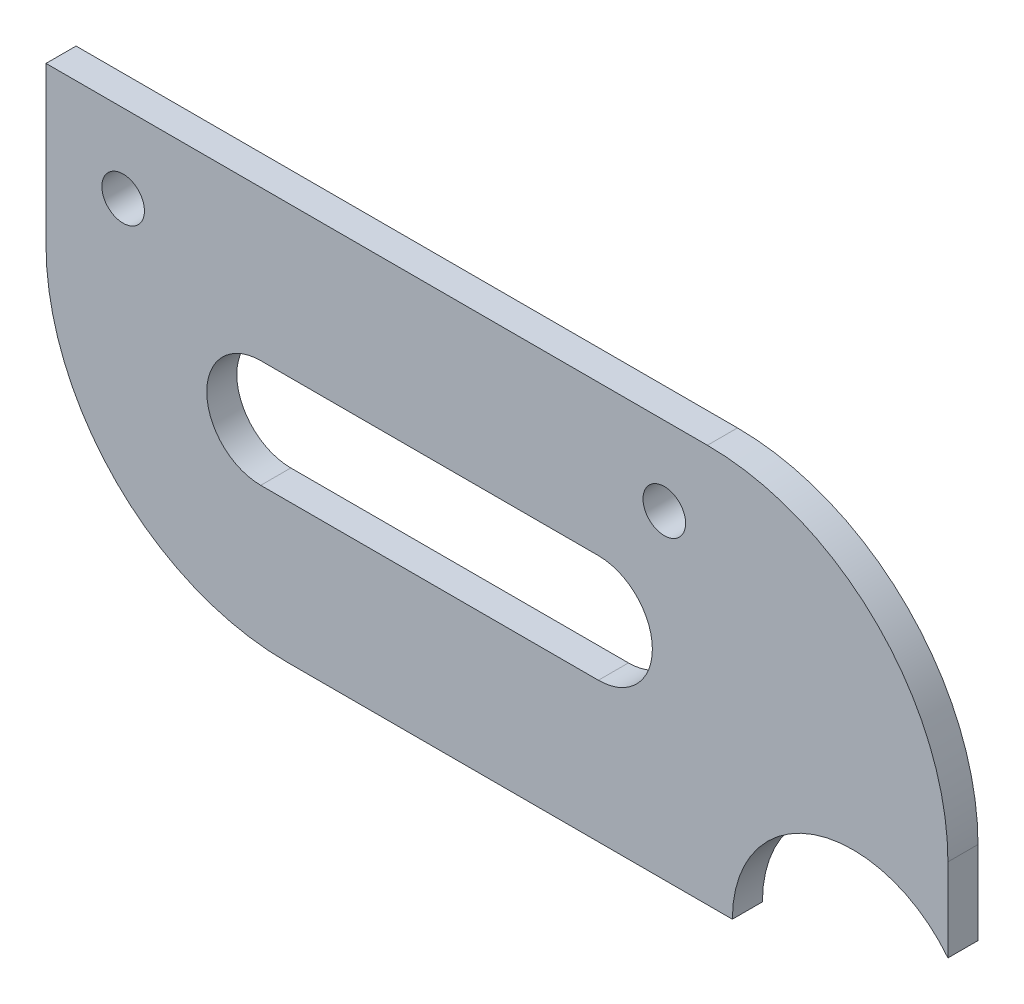
SolidWorks part; units mm, degrees
material "AISI 4130 Steel, annealed at 865C"
ref_plane "Front Plane" through (0, 0, 0) normal (0, 0, 1) x (1, 0, 0)
ref_plane "Top Plane" through (0, 0, 0) normal (0, 1, 0) x (1, 0, 0)
ref_plane "Right Plane" through (0, 0, 0) normal (1, 0, 0) x (0, 0, -1)
sketch "Sketch1" plane through (0, 0, 0) normal (0, 0, 1) x (1, 0, 0)
  line L1 (-14.4972, -4.4056) -> (80.7528, -4.4056)
  line L2 (-14.4972, -4.4056) -> (-14.4972, -46.4382)
  line L4 (80.7528, -4.4056) -> (80.7528, -38.5964)
  line L5 (57.9856, -46.4382) -> (-14.4972, -46.4382)
  line L6 (8.1801, -25.9546) -> (43.8381, -25.9546) construction
  line L7 (8.1801, -20.2546) -> (43.8381, -20.2546)
  line L8 (8.1801, -31.6545) -> (43.8381, -31.6545)
  arc A3 (80.7528, -38.5964) -> (57.9856, -46.4382) centre (70.7197, -46.4382) ccw
  arc A4 (8.1801, -20.2546) -> (8.1801, -31.6545) centre (8.1801, -25.9546) ccw
  arc A5 (43.8381, -31.6545) -> (43.8381, -20.2546) centre (43.8381, -25.9546) ccw
  point P5 (26.0091, -25.9546)
  dimension "D1" = 95.25
extrude "Boss-Extrude1" add sketch "Sketch1" along normal blind 3.175
fillet "Fillet1" radius 25.4 2 edges at (-14.4972, -46.4382, 1.5875) (80.7528, -4.4056, 1.5875)
sketch "Sketch2" plane through (0, 0, 0) normal (0, 0, -1) x (-1, 0, 0)
  circle A0 centre (-50.8, -12.699) radius 2.25 construction
  circle A1 centre (6.35, -12.699) radius 2.25 construction
  circle A2 centre (-50.8, -12.699) radius 2.25
  circle A3 centre (6.35, -12.699) radius 2.25
extrude "Cut-Extrude1" cut sketch "Sketch2" against normal through all
